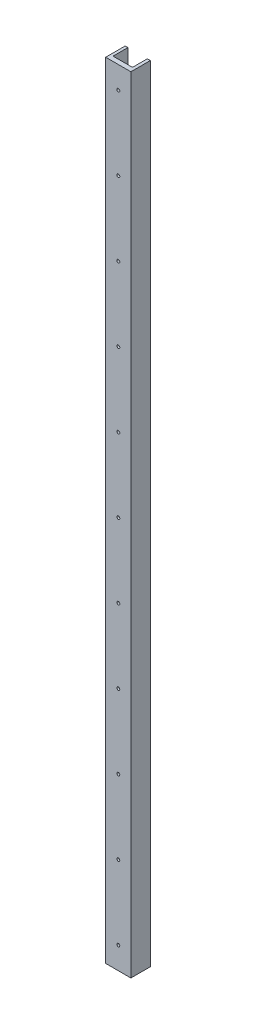
SolidWorks part; units mm, degrees
material "6061-T6 (SS)"
ref_plane "Front Plane" through (0, 0, 0) normal (0, 0, 1) x (1, 0, 0)
ref_plane "Top Plane" through (0, 0, 0) normal (0, 1, 0) x (1, 0, 0)
ref_plane "Right Plane" through (0, 0, 0) normal (1, 0, 0) x (0, 0, -1)
sketch "Sketch1" plane through (0, 0, 0) normal (0, 0, 1) x (1, 0, 0)
  line L1 (-43.18, -1221.28) -> (0, -1221.28)
  line L2 (-43.18, -1221.28) -> (-43.18, 124.92)
  line L3 (-43.18, 124.92) -> (0, 124.92)
  line L4 (0, -1221.28) -> (0, 124.92)
  dimension "D1" = 43.18
  dimension "D2" = 1346.2
extrude "Boss-Extrude1" add sketch "Sketch1" along normal blind 33.3248
sketch "Sketch9" plane through (0, 124.92, 0) normal (0, 1, 0) x (1, 0, 0)
  line L1 (-38.481, 7.7343) -> (-5.1435, 7.7343)
  line L2 (-38.481, 7.7343) -> (-38.481, -25.3873)
  line L3 (-38.481, -25.3873) -> (-5.1435, -25.3873)
  line L4 (-5.1435, 7.7343) -> (-5.1435, -25.3873)
  dimension "D1" = 7.9375
  dimension "D2" = 33.3375
  dimension "D3" = 4.699
extrude "Cut-Extrude1" cut sketch "Sketch9" against normal through all contours L3 L4 L1 L2
sketch "Sketch10" plane through (0, 0, 33.3248) normal (0, 0, 1) x (1, 0, 0)
  line L0 (-21.59, -1183.18) -> (-21.59, -1056.18) construction
  circle A0 centre (-21.59, -1183.18) radius 2.9208
  circle A1 centre (-21.59, -1056.18) radius 2.9208
  circle A2 centre (-21.59, -929.18) radius 2.9208
  circle A3 centre (-21.59, -802.18) radius 2.9208
  circle A4 centre (-21.59, -675.18) radius 2.9208
  circle A5 centre (-21.59, -548.18) radius 2.9208
  circle A6 centre (-21.59, -421.18) radius 2.9208
  circle A7 centre (-21.59, -294.18) radius 2.9208
  circle A8 centre (-21.59, -167.18) radius 2.9208
  circle A9 centre (-21.59, -40.18) radius 2.9208
  circle A10 centre (-21.59, 86.82) radius 2.9208
  dimension "D1" = 21.59
  dimension "D2" = 38.1
  dimension "D4" = 127
  dimension "D3" = 11
hole_wizard "CSK for #10 Flat Head Machine Screw3" positions "Sketch12" profile "Sketch11" countersink size "#10" standard "ANSI Inch"
sketch "Sketch12" plane through (0, 0, 25.3873) normal (0, 0, -1) x (-1, 0, 0)
  point P0 (21.59, -1183.18)
  point P3 (21.59, -1056.18)
  point P6 (21.59, -929.18)
  point P9 (21.59, -929.18)
  point P11 (21.59, -802.18)
  point P14 (21.59, -675.18)
  point P17 (21.59, -548.18)
  point P20 (21.59, -421.18)
  point P23 (21.59, -294.18)
  point P26 (21.59, -167.18)
  point P29 (21.59, -40.18)
  point P32 (21.59, 86.82)
sketch "Sketch11" plane through (-21.59, -1183.18, 25.3873) normal (1, 0, 0) x (0, 1, 0)
  line L0 (0, 0) -> (0, 77.7338)
  line L1 (0, 77.7338) -> (2.5527, 76.2)
  line L2 (2.5527, 76.2) -> (2.5527, 2.9422)
  line L3 (2.5527, 2.9422) -> (5.1103, 0)
  line L5 (5.1103, 0) -> (0, 0)
  line L6 (-2.5527, 2.9422) -> (-5.1103, 0) construction
  line L10 (0, 77.7338) -> (-2.5527, 76.2) construction
  line L11 (0, -6.35) -> (0, 107.95) construction
  dimension "Hole Dia." = 5.1054
  dimension "Hole Depth" = 76.2
  dimension "Near C'Sink Dia." = 10.2206
  dimension "Near C'Sink Angle" = 82
  dimension "Drill Angle" = 118
